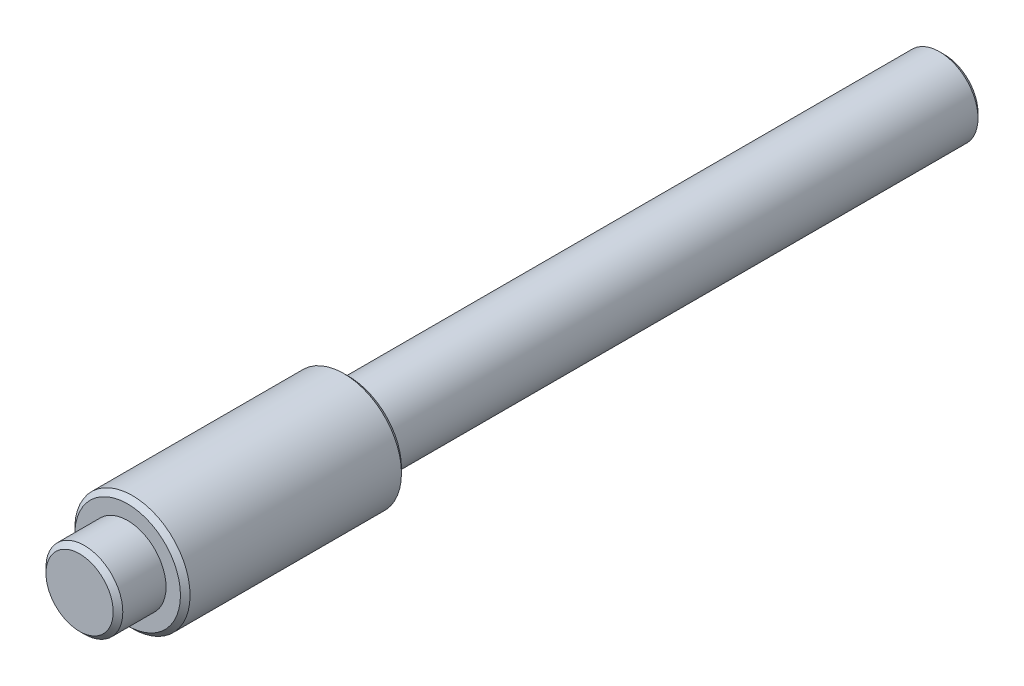
SolidWorks part; units mm, degrees
ref_plane "Front Plane" through (0, 0, 0) normal (0, 0, 1) x (1, 0, 0)
ref_plane "Top Plane" through (0, 0, 0) normal (0, 1, 0) x (1, 0, 0)
ref_plane "Right Plane" through (0, 0, 0) normal (1, 0, 0) x (0, 0, -1)
sketch "Sketch1" plane through (0, 0, 0) normal (0, 1, 0) x (1, 0, 0)
  line L0 (3.5, 0) -> (0, 0)
  line L1 (0, 0) -> (0, -90)
  line L2 (0, -90) -> (3.5, -90)
  line L3 (3.5, -90) -> (4, -89.5)
  line L4 (4, -89.5) -> (4, -85)
  line L5 (4, -85) -> (5.5, -85)
  line L6 (5.5, -85) -> (6, -84.5)
  line L7 (6, -84.5) -> (6, -62.5)
  line L8 (6, -62.5) -> (5.5, -62)
  line L9 (5.5, -62) -> (4, -62)
  line L10 (4, -62) -> (4, -0.5)
  line L11 (4, -0.5) -> (3.5, 0)
  line L12 (0, 0) -> (0, -90) construction
revolve "Revolve1" add sketch "Sketch1" angle 360 about L12
